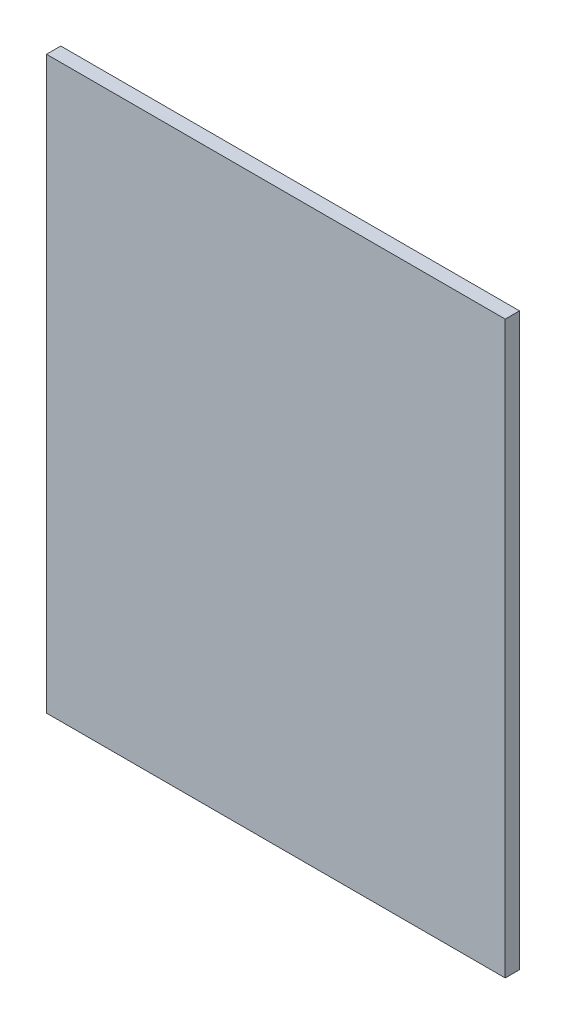
SolidWorks part; units mm, degrees
ref_plane "Спереди" through (0, 0, 0) normal (0, 0, 1) x (1, 0, 0)
ref_plane "Сверху" through (0, 0, 0) normal (0, 1, 0) x (1, 0, 0)
ref_plane "Справа" through (0, 0, 0) normal (1, 0, 0) x (0, 0, -1)
sketch "Эскиз1" plane through (0, 0, 0) normal (0, 1, 0) x (1, 0, 0)
  line L0 (78.3969, -2.5) -> (78.3969, 0)
  line L1 (-1.9933, 0) -> (78.3969, 0)
  line L2 (-1.9933, 0) -> (-1.9933, -2.5)
  line L3 (-1.9933, -2.5) -> (78.3969, -2.5)
extrude "Вытянуть1" add sketch "Эскиз1" along normal blind 100
